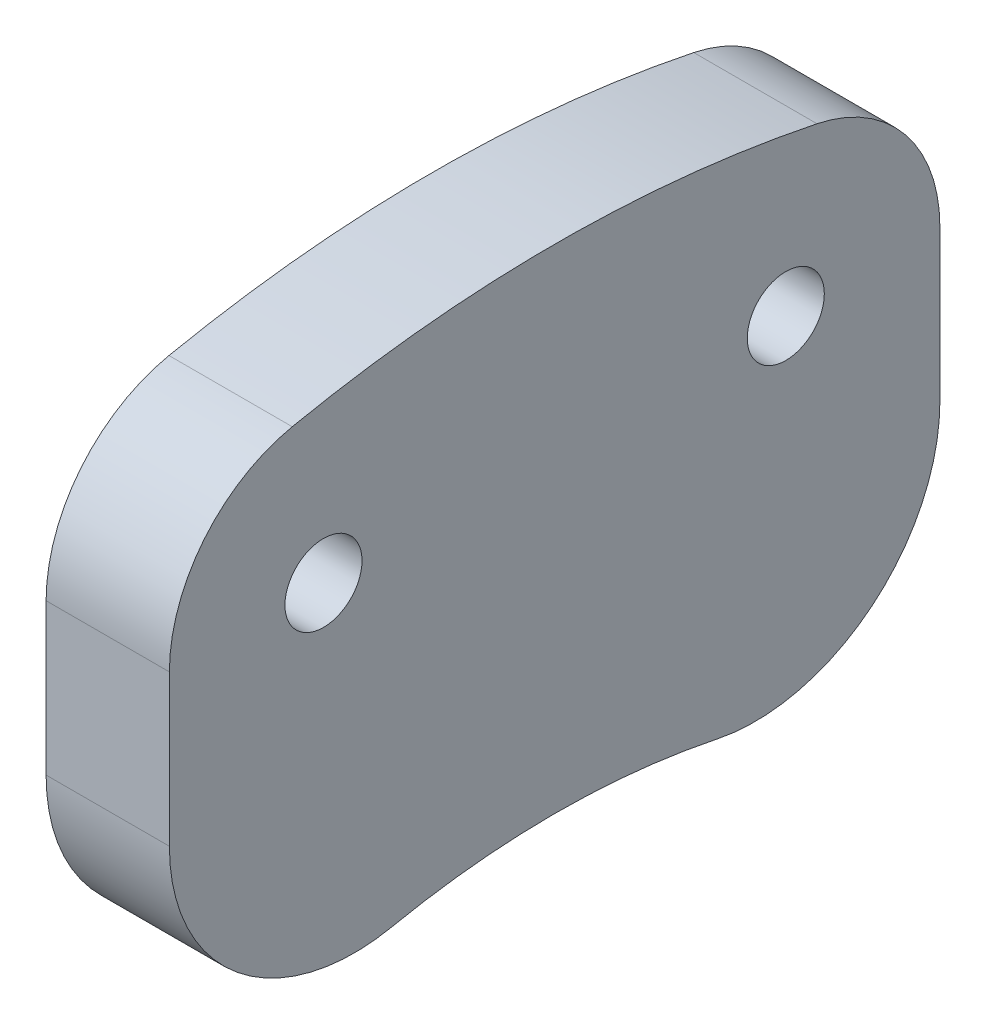
SolidWorks part; units mm, degrees
material "5052-H32"
ref_plane "Front Plane" through (0, 0, 0) normal (0, 0, 1) x (1, 0, 0)
ref_plane "Top Plane" through (0, 0, 0) normal (0, 1, 0) x (1, 0, 0)
ref_plane "Right Plane" through (0, 0, 0) normal (1, 0, 0) x (0, 0, -1)
sketch "Sketch2" plane through (0, 0, 0) normal (1, 0, 0) x (0, 0, -1)
  line L0 (-12.5, 9.8053) -> (-12.5, -3.6285) construction
  line L1 (12.5, 9.8053) -> (12.5, -3.6285) construction
  line L2 (-12.5, 9.8053) -> (-12.5, -3.6285)
  line L3 (12.5, 9.8053) -> (12.5, -3.6285)
  circle A0 centre (0, 10.5734) radius 3 construction
  circle A1 centre (0, -26.4266) radius 26 construction
  arc A2 (8.5135, 14.7015) -> (-8.5135, 14.7015) centre (0, -26.4266) ccw construction
  arc A3 (-8.5135, 14.7015) -> (-12.5, 9.8053) centre (-7.5, 9.8053) ccw construction
  arc A4 (12.5, 9.8053) -> (8.5135, 14.7015) centre (7.5, 9.8053) ccw construction
  circle A5 centre (0, 10.5734) radius 3
  arc A6 (12.5, -3.6285) -> (-12.5, -3.6285) centre (0, -26.4266) ccw
  arc A7 (8.5135, 14.7015) -> (-8.5135, 14.7015) centre (0, -26.4266) ccw
  arc A8 (-8.5135, 14.7015) -> (-12.5, 9.8053) centre (-7.5, 9.8053) ccw
  arc A9 (12.5, 9.8053) -> (8.5135, 14.7015) centre (7.5, 9.8053) ccw
extrude "Boss-Extrude1" add sketch "Sketch2" along normal up to vertex (4 mm away) contours A5 | L3 A9 A7 A8 L2 A6 A5
fillet "Fillet1" radius 6 2 edges at (2, -3.6285, 12.5) (2, -3.6285, -12.5)
hole_wizard "M3x0.5 Tapped Hole1" positions "Sketch3" profile "Sketch4" tap size "M3x0.5" standard "ANSI Metric" end condition up to next
sketch "Sketch3" plane through (0, 0, 0) normal (-1, 0, 0) x (0, 0, 1)
  point P0 (-7.5, 9.8053)
  point P3 (7.5, 9.8053)
sketch "Sketch4" plane through (0, 9.8053, -7.5) normal (0, 1, 0) x (0, 0, 1)
  line L0 (0, 0) -> (0, 4)
  line L1 (0, 4) -> (1.25, 4)
  line L2 (1.25, 4) -> (1.25, 0)
  line L5 (1.25, 0) -> (0, 0)
  line L11 (0, -6.35) -> (0, 107.95) construction
  dimension "Thru Tap Drill Dia." = 2.5
  dimension "Thru Tap Drill Depth" = 4
cosmetic thread "Hole Thread1" parameters "D2"=3
cosmetic thread "Hole Thread2" parameters "D2"=3
